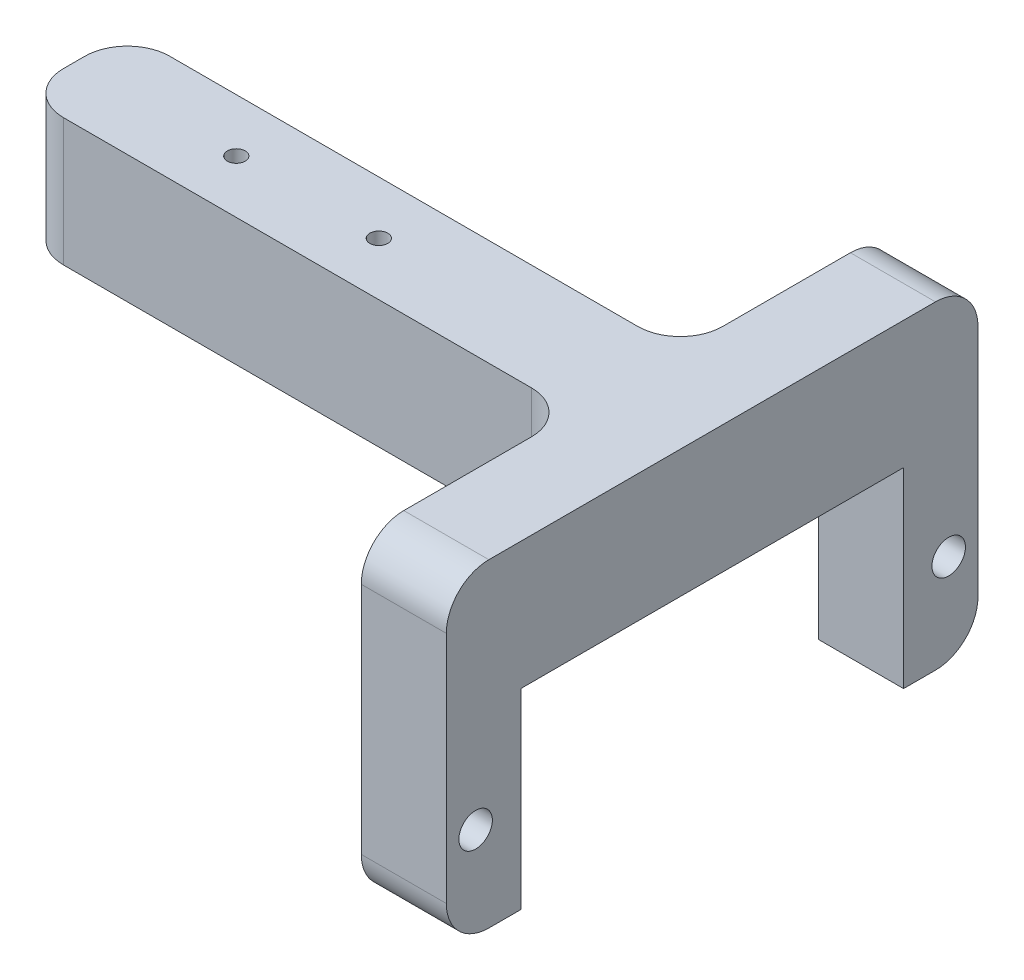
SolidWorks part; units mm, degrees
ref_plane "Front Plane" through (0, 0, 0) normal (0, 0, 1) x (1, 0, 0)
ref_plane "Top Plane" through (0, 0, 0) normal (0, 1, 0) x (1, 0, 0)
ref_plane "Right Plane" through (0, 0, 0) normal (1, 0, 0) x (0, 0, -1)
sketch "Sketch2" plane through (0, 0, 0) normal (0, 1, 0) x (1, 0, 0)
  line L1 (-19.05, -3.175) -> (19.05, -3.175)
  line L2 (-19.05, -3.175) -> (-19.05, 3.175)
  line L3 (-19.05, 3.175) -> (19.05, 3.175)
  line L4 (19.05, -3.175) -> (19.05, 3.175)
  line L5 (-19.05, -3.175) -> (19.05, 3.175) construction
  line L6 (-19.05, 3.175) -> (19.05, -3.175) construction
  point P0 (0, 0)
  dimension "D1" = 38.1
  dimension "D2" = 6.35
extrude "Boss-Extrude1" add sketch "Sketch2" along normal blind 7.62
sketch "Sketch3" plane through (0, 0, -3.175) normal (0, 0, -1) x (-1, 0, 0)
  line L0 (-19.05, 0) -> (19.05, 0) construction
  line L1 (-19.05, 7.62) -> (-13.97, 7.62)
  line L2 (-19.05, 7.62) -> (-19.05, 0)
  line L3 (-19.05, 0) -> (-13.97, 0)
  line L4 (-13.97, 7.62) -> (-13.97, 0)
  dimension "D1" = 5.08
extrude "Boss-Extrude2" add sketch "Sketch3" along normal blind 12.7
mirror "Mirror1" about plane through (0, 0, 0) normal (0, 0, 1) of "Boss-Extrude2"
sketch "Sketch4" plane through (0, 0, 0) normal (0, -1, 0) x (1, 0, 0)
  line L0 (19.05, 0) -> (19.0749, 0) construction
  line L1 (19.05, 15.875) -> (19.05, -15.875) construction
  line L2 (19.05, 11.43) -> (13.97, 11.43)
  line L3 (13.97, 15.875) -> (13.97, 3.175) construction
  line L4 (19.05, -11.43) -> (13.97, -11.43)
  line L6 (19.05, 11.43) -> (13.97, 11.43)
  line L7 (19.05, 11.43) -> (19.05, 15.875)
  line L8 (19.05, 15.875) -> (13.97, 15.875)
  line L9 (13.97, 11.43) -> (13.97, 15.875)
  line L10 (19.05, -11.43) -> (13.97, -11.43)
  line L11 (19.05, -11.43) -> (19.05, -15.875)
  line L12 (19.05, -15.875) -> (13.97, -15.875)
  line L13 (13.97, -11.43) -> (13.97, -15.875)
  line M3 (19.05, -15.875) -> (19.05, 15.875)
  line M4 (19.05, 15.875) -> (13.97, 15.875)
  line M5 (13.97, 15.875) -> (13.97, 3.175)
  line M9 (13.97, -3.175) -> (13.97, -15.875)
  line M10 (13.97, -15.875) -> (19.05, -15.875)
  dimension "D1" = 11.43
extrude "Boss-Extrude3" add sketch "Sketch4" along normal blind 11.43 contours L2 M3 M4 M5 | L4 M3 M9 M10
sketch "Sketch5" plane through (0, 7.62, 0) normal (0, 1, 0) x (1, 0, 0)
  line L0 (13.97, 3.175) -> (-19.05, 3.175) construction
  line L1 (-19.05, 3.175) -> (-19.05, -3.175) construction
  circle A1 centre (-15.875, 0) radius 0.762
  dimension "D1" = 3.175
  dimension "D2" = 3.175
sketch "Sketch6" plane through (19.05, 0, 0) normal (1, 0, 0) x (0, 0, -1)
  arc A0 (14.991, -5.45) -> (14.991, -6.45) centre (14.125, -5.95) ccw construction
  arc A1 (-14.991, -6.45) -> (-14.991, -5.45) centre (-14.125, -5.95) ccw construction
  arc A2 (14.991, -5.45) -> (14.991, -6.45) centre (14.125, -5.95) ccw
  arc A3 (-14.991, -6.45) -> (-14.991, -5.45) centre (-14.125, -5.95) ccw
  circle A4 centre (-14.125, -5.95) radius 1
  circle A5 centre (14.125, -5.95) radius 1
extrude "Cut-Extrude2" cut sketch "Sketch6" against normal through all contours A3 A4 | A2 A5
fillet "Fillet1" radius 2.54 8 edges at (16.51, 7.62, 15.875) (16.51, -11.43, 15.875) (16.51, 7.62, -15.875) (16.51, -11.43, -15.875) (13.97, 3.81, 3.175) (13.97, 3.81, -3.175) (-19.05, 3.81, 3.175) (-19.05, 3.81, -3.175)
sketch "Sketch8" plane through (0, 0, 0) normal (0, -1, 0) x (1, 0, 0)
  circle A0 centre (-0.8573, 0) radius 0.5334 construction
  circle A1 centre (-9.3663, 0) radius 0.5334 construction
  circle A2 centre (-0.8573, 0) radius 0.5334
  circle A3 centre (-9.3663, 0) radius 0.5334
extrude "Cut-Extrude4" cut sketch "Sketch8" against normal through all
